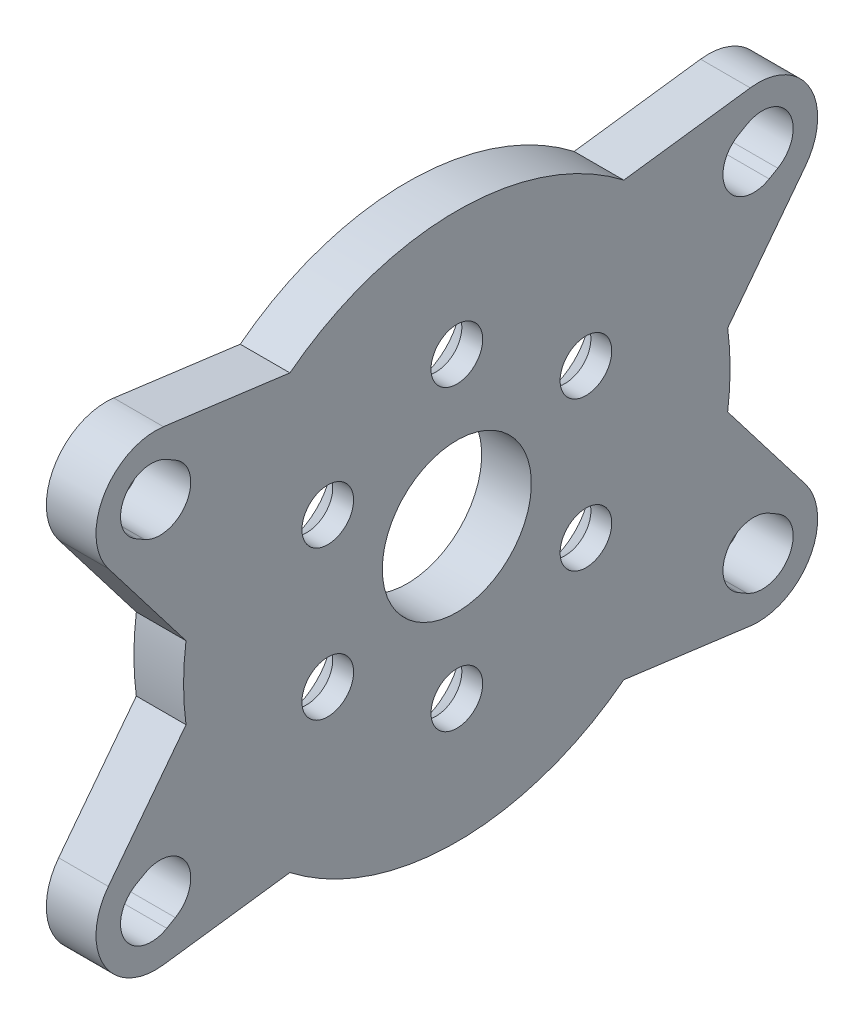
SolidWorks part; units mm, degrees
material "Ti-5Al-2.5Sn Отожженный (SS)"
ref_plane "Спереди" through (0, 0, 0) normal (0, 0, 1) x (1, 0, 0)
ref_plane "Сверху" through (0, 0, 0) normal (0, 1, 0) x (1, 0, 0)
ref_plane "Справа" through (0, 0, 0) normal (1, 0, 0) x (0, 0, -1)
sketch "Эскиз1" plane through (0, 0, 0) normal (0, 0, 1) x (1, 0, 0)
  line L0 (0, 7.5) -> (0, 27.5)
  line L1 (0, 27.5) -> (5, 27.5)
  line L2 (5, 27.5) -> (5, 7.5)
  line L3 (5, 7.5) -> (0, 7.5)
  line L4 (-29.3651, 0) -> (90.6978, 0) construction
  dimension "D1" = 15
  dimension "D2" = 55
  dimension "D3" = 5
revolve "Повернуть1" add sketch "Эскиз1" angle 360 about L4
sketch "Эскиз11" plane through (0, 0, 0) normal (-1, 0, 0) x (0, 0, 1)
  line L0 (-5.5433, 37.2961) -> (-10.4565, 25.4344)
  line L1 (0, 35) -> (0, 0) construction
  line L2 (5.5433, 37.2961) -> (10.4565, 25.4344)
  line L3 (0, 0) -> (0, 50000) construction
  line L4 (0, 0) -> (-50000, 0) construction
  circle A1 centre (0, 0) radius 35 construction
  arc A2 (10.4565, 25.4344) -> (-10.4565, 25.4344) centre (0, 0) ccw
  arc A3 (-5.5433, 37.2961) -> (5.5433, 37.2961) centre (0, 35) cw
  circle A4 centre (0, 0) radius 27.5 construction
  dimension "D1" = 70
  dimension "D2" = 6
  dimension "D3" = 45
  dimension "D4" = 0
extrude "Бобышка-Вытянуть1" add sketch "Эскиз11" against normal blind 5
pattern_circular "Круговой массив3" count 3 every 60 about axis through (0, 0, 0) along (1, 0, 0) of "Бобышка-Вытянуть1"
sketch "Эскиз6" plane through (0, 0, 0) normal (-1, 0, 0) x (0, 0, 1)
  line L0 (-3.1, 35.5) -> (-3.1, 34.5)
  line L1 (3.1, 35.5) -> (3.1, 34.5)
  line L2 (0, 0) -> (0, 50000) construction
  line L3 (0, 0) -> (-50000, 0) construction
  line L4 (-3.1, 35) -> (3.1, 35) construction
  line L5 (0, 22.5) -> (0, -49977.5) construction
  arc A0 (3.1, 35.5) -> (-3.1, 35.5) centre (0, 35.5) ccw
  arc A1 (-3.1, 34.5) -> (3.1, 34.5) centre (0, 34.5) ccw
  circle A2 centre (0, 0) radius 35 construction
  point P11 (0, 35)
  dimension "D1" = 1
  dimension "D3" = 70
  dimension "D2" = 6.2
  dimension "D4" = 0
extrude "Вырез-Вытянуть3" cut sketch "Эскиз6" against normal through all both and the other way through all
pattern_circular "Круговой массив2" count 3 every 60 about axis through (0, 0, 0) along (1, 0, 0) of "Вырез-Вытянуть3"
sketch "Эскиз9" plane through (0, 0, 0) normal (-1, 0, 0) x (0, 0, 1)
  circle A0 centre (0, 0) radius 15 construction
  point P0 (0, 15)
  point P33 (12.9904, 7.5)
  point P34 (12.9904, -7.5)
  point P35 (0, -15)
  point P36 (-12.9904, -7.5)
  point P37 (-12.9904, 7.5)
  dimension "D2" = 30
  dimension "D1" = 6
hole_wizard "Зенковка для винта с потайной головкой и внутренним шестигранником M51" positions "Эскиз9" profile "Эскиз10" countersink size "M5" standard "DIN" end condition through all
sketch "Эскиз10" plane through (0, 15, 0) normal (0, 1, 0) x (0, 0, 1)
  line L0 (0, 0) -> (0, 5)
  line L1 (0, 5) -> (2.6, 5)
  line L2 (2.6, 5) -> (2.6, 2.9)
  line L3 (2.6, 2.9) -> (5.5, 0)
  line L5 (5.5, 0) -> (0, 0)
  line L6 (-2.6, 2.9) -> (-5.5, 0) construction
  line L11 (0, -6.35) -> (0, 107.95) construction
  dimension "Диаметр сквозного отверстия" = 5.2
  dimension "Глубина сквозного отверстия" = 5
  dimension "Диаметр передней зенковки" = 11
  dimension "Угол передней зенковки" = 90
sketch "Эскиз12" plane through (0, 0, 0) normal (-1, 0, 0) x (0, 0, 1)
  line L0 (10.4565, 25.4344) -> (5.5433, 37.2961) construction
  line L1 (-5.5433, 37.2961) -> (-10.4565, 25.4344) construction
  line L2 (10.4565, 25.4344) -> (5.5433, 37.2961)
  line L3 (-5.5433, 37.2961) -> (-10.4565, 25.4344)
  arc A0 (10.4565, 25.4344) -> (-10.4565, 25.4344) centre (0, 0) ccw
  arc A1 (5.5433, 37.2961) -> (-5.5433, 37.2961) centre (0, 35) ccw construction
  arc A2 (5.5433, 37.2961) -> (-5.5433, 37.2961) centre (0, 35) ccw
extrude "Вырез-Вытянуть4" cut sketch "Эскиз12" against normal through all
